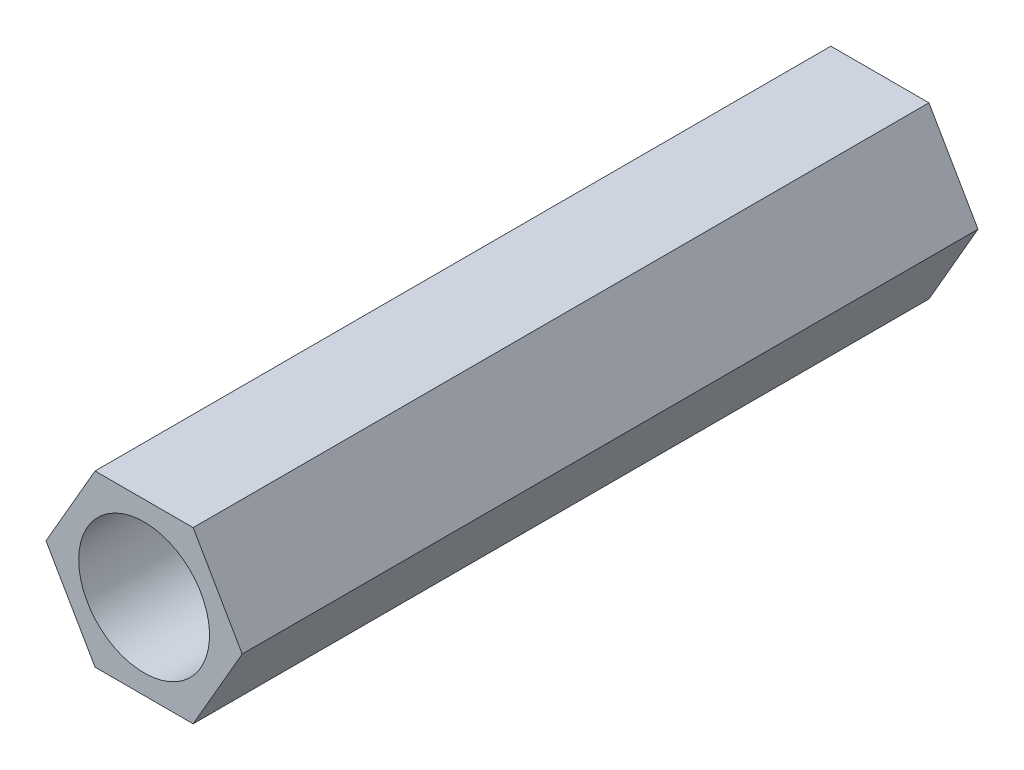
SolidWorks part; units mm, degrees
ref_plane "前视基准面" through (0, 0, 0) normal (0, 0, 1) x (1, 0, 0)
ref_plane "上视基准面" through (0, 0, 0) normal (0, 1, 0) x (1, 0, 0)
ref_plane "右视基准面" through (0, 0, 0) normal (1, 0, 0) x (0, 0, -1)
other "Configuration Table"
ref_plane "基准面1" through (0, 0, 0) normal (0, 0, -1) x (-1, 0, 0)
sketch "草图1" plane through (0, 0, 0) normal (0, 0, -1) x (-1, 0, 0)
  line L0 (1.5, -2.5981) -> (3, 0)
  line L1 (3, 0) -> (1.5, 2.5981)
  line L2 (1.5, 2.5981) -> (-1.5, 2.5981)
  line L3 (-1.5, 2.5981) -> (-3, 0)
  line L4 (-3, 0) -> (-1.5, -2.5981)
  line L5 (-1.5, -2.5981) -> (1.5, -2.5981)
  circle A0 centre (0, 0) radius 2
  dimension "D1" = 4
  dimension "D2" = 1.5
  dimension "D3" = 3
  dimension "D4" = 4.5
  dimension "D5" = 6
  dimension "D6" = 2.5981
  dimension "D7" = 5.1962
extrude "凸台-拉伸1" add sketch "草图1" against normal blind 22.5
